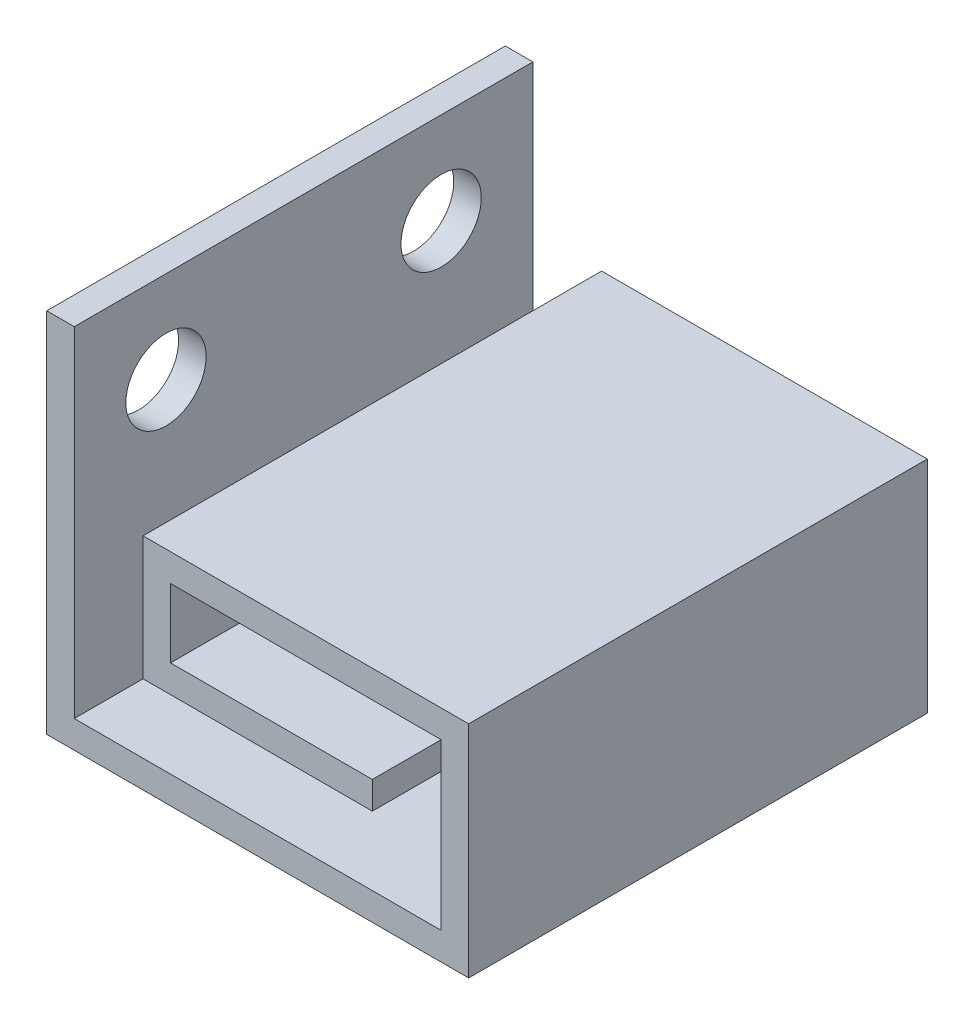
SolidWorks part; units mm, degrees
ref_plane "Front Plane" through (0, 0, 0) normal (0, 0, 1) x (1, 0, 0)
ref_plane "Top Plane" through (0, 0, 0) normal (0, 1, 0) x (1, 0, 0)
ref_plane "Right Plane" through (0, 0, 0) normal (1, 0, 0) x (0, 0, -1)
sketch "Sketch1" plane through (0, 0, 0) normal (0, 0, 1) x (1, 0, 0)
  line L0 (0, 0) -> (18.4, 0)
  line L1 (18.4, 0) -> (18.4, 9.6)
  line L2 (18.4, 9.6) -> (4.2, 9.6)
  line L3 (4.2, 9.6) -> (4.2, 4.2)
  line L4 (4.2, 4.2) -> (14.2, 4.2)
  line L5 (0, 0) -> (0, 16)
  line L6 (0, 16) -> (1.2, 16)
  line L7 (1.2, 16) -> (1.2, 1.2)
  line L8 (1.2, 1.2) -> (1.2, 0) construction
  line L9 (1.2, 1.2) -> (17.2, 1.2)
  line L10 (17.2, 1.2) -> (18.4, 1.2) construction
  line L11 (17.2, 1.2) -> (17.2, 8.4)
  line L12 (17.2, 8.4) -> (17.2, 9.6) construction
  line L13 (17.2, 8.4) -> (5.4, 8.4)
  line L14 (5.4, 8.4) -> (4.2, 8.4) construction
  line L15 (5.4, 8.4) -> (5.4, 5.4)
  line L16 (5.4, 5.4) -> (5.4, 4.2) construction
  line L17 (5.4, 5.4) -> (14.2, 5.4)
  line L18 (14.2, 5.4) -> (14.2, 4.2)
  point P3 (14.2, 4.8)
  point P9 (0, 11)
  point P22 (17.4555, 0)
  dimension "D1" = 16
  dimension "D2" = 5
  dimension "D3" = 1.2
  dimension "D4" = 3
  dimension "D5" = 3
  dimension "D6" = 3
  dimension "D7" = 3
  dimension "D8" = 10
extrude "Boss-Extrude1" add sketch "Sketch1" along normal mid plane 20
sketch "Sketch2" plane through (1.2, 0, 0) normal (1, 0, 0) x (0, 0, -1)
  line L0 (-6, 12) -> (6, 12) construction
  line L1 (0, 12) -> (0, 0) construction
  line L2 (-10, 16) -> (10, 16) construction
  circle A0 centre (-6, 12) radius 1.75
  circle A1 centre (6, 12) radius 1.75
  dimension "D1" = 4
  dimension "D2" = 3.5
  dimension "D3" = 12
extrude "Cut-Extrude1" cut sketch "Sketch2" against normal mid plane 20
equation "\"D4@Sketch1\"=\"D6@Sketch1\""
equation "\"D7@Sketch1\"=\"D6@Sketch1\""
equation "\"D5@Sketch1\"=\"D6@Sketch1\""
